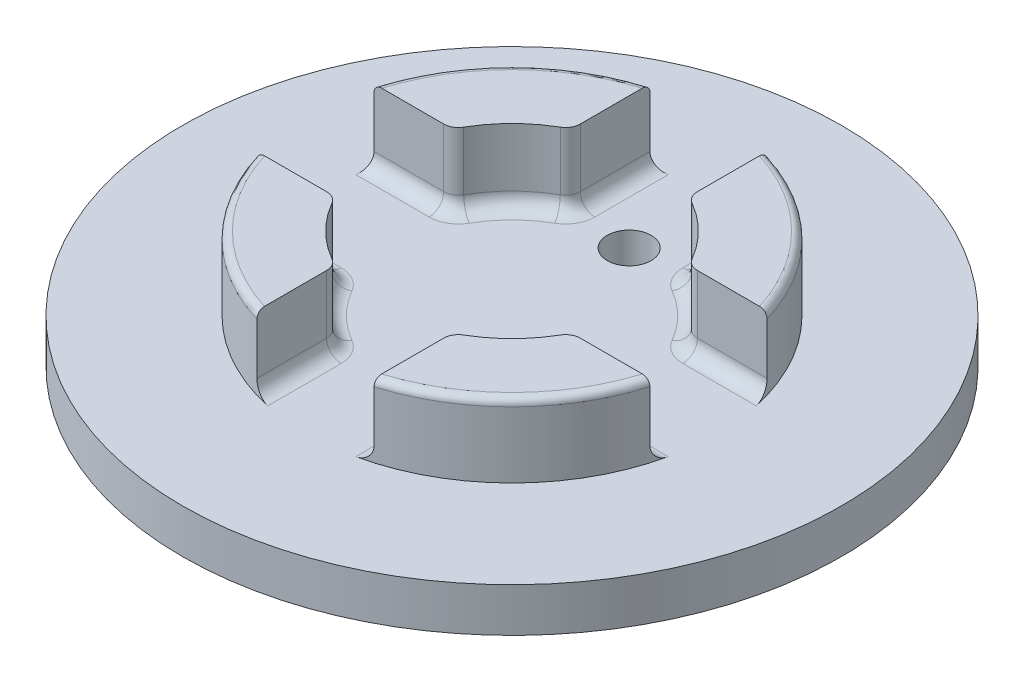
SolidWorks part; units mm, degrees
ref_plane "Front Plane" through (0, 0, 0) normal (0, 0, 1) x (1, 0, 0)
ref_plane "Top Plane" through (0, 0, 0) normal (0, 1, 0) x (1, 0, 0)
ref_plane "Right Plane" through (0, 0, 0) normal (1, 0, 0) x (0, 0, -1)
sketch "Sketch2" plane through (0, 0, 0) normal (0, 1, 0) x (1, 0, 0)
  circle A0 centre (0, 0) radius 22.5
  dimension "D1" = 45
extrude "Boss-Extrude1" add sketch "Sketch2" along normal blind 3
sketch "Sketch3" plane through (0, 3, 0) normal (0, 1, 0) x (1, 0, 0)
  line L1 (-22.5, 4) -> (22.5, 4)
  line L2 (-22.5, 4) -> (-22.5, -4)
  line L3 (-22.5, -4) -> (22.5, -4)
  line L4 (22.5, 4) -> (22.5, -4)
  line L5 (-4, 22.5) -> (4, 22.5)
  line L6 (-4, 22.5) -> (-4, -22.5)
  line L7 (-4, -22.5) -> (4, -22.5)
  line L8 (4, 22.5) -> (4, -22.5)
  circle A0 centre (0, 0) radius 14
  circle A2 centre (0, 0) radius 22.5 construction
  circle A3 centre (0, 0) radius 9
  point P13 (22.5, 0)
  point P15 (0, 22.5)
  dimension "D1" = 28
  dimension "D2" = 5
  dimension "D3" = 8
extrude "Boss-Extrude2" add sketch "Sketch3" along normal blind 5 contours A3 L6 A0 L1 | A3 L1 A0 L8 | A3 L8 A0 L3 | A3 L3 A0 L6
fillet "Fillet1" radius 1 20 edges at (-4, 3, 10.7393) (-4, 3, -10.7393) (-10.7393, 3, 4) (10.7393, 3, 4) (4, 3, 10.7393) (4, 3, -10.7393) (10.7393, 3, -4) (-10.7393, 3, -4) (-6.364, 3, 6.364) (6.364, 3, 6.364) (6.364, 3, -6.364) (-6.364, 3, -6.364) (4, 5.5, 8.0623) (8.0623, 5.5, 4) (4, 5.5, -8.0623) (8.0623, 5.5, -4) (-4, 5.5, -8.0623) (-8.0623, 5.5, -4) (-8.0623, 5.5, 4) (-4, 5.5, 8.0623)
fillet "Fillet2" radius 0.5 4 edges at (9.8995, 8, -9.8995) (-9.8995, 8, -9.8995) (-9.8995, 8, 9.8995) (9.8995, 8, 9.8995)
sketch "Sketch5" plane through (0, 3, 0) normal (0, 1, 0) x (1, 0, 0)
  circle A0 centre (0, 8) radius 1.5
  point P2 (0, 0)
  dimension "D1" = 3
  dimension "D2" = 8
extrude "Cut-Extrude1" cut sketch "Sketch5" against normal blind 5
